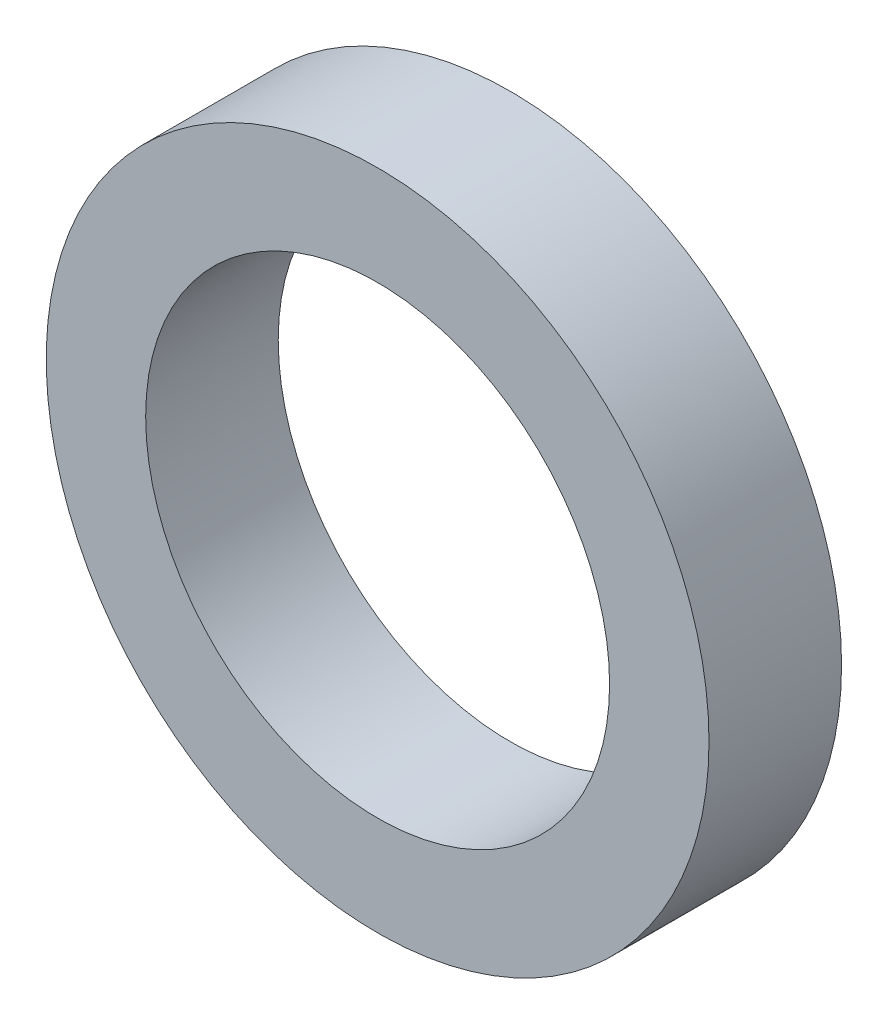
SolidWorks part; units mm, degrees
ref_plane "Спереди" through (0, 0, 0) normal (0, 0, 1) x (1, 0, 0)
ref_plane "Сверху" through (0, 0, 0) normal (0, 1, 0) x (1, 0, 0)
ref_plane "Справа" through (0, 0, 0) normal (1, 0, 0) x (0, 0, -1)
sketch "Эскиз1" plane through (0, 0, 0) normal (0, 0, 1) x (1, 0, 0)
  circle A0 centre (0, 0) radius 20
  circle A1 centre (0, 0) radius 14
  dimension "D1" = 28
  dimension "D2" = 40
extrude "Бобышка-Вытянуть1" add sketch "Эскиз1" along normal blind 8
